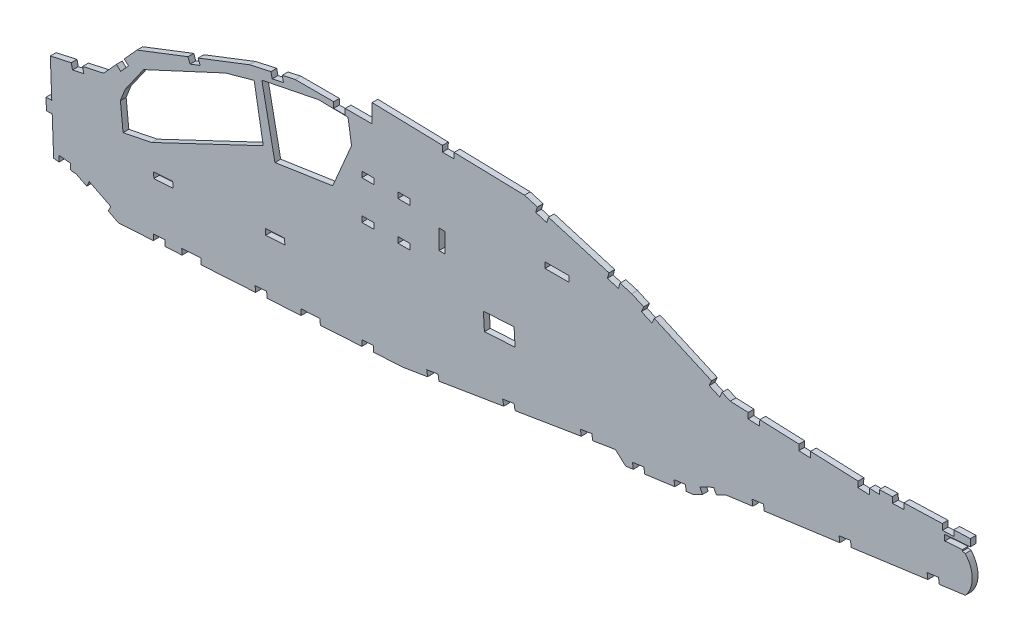
SolidWorks part; units mm, degrees
ref_plane "Front Plane" through (0, 0, 0) normal (0, 0, 1) x (1, 0, 0)
ref_plane "Top Plane" through (0, 0, 0) normal (0, 1, 0) x (1, 0, 0)
ref_plane "Right Plane" through (0, 0, 0) normal (1, 0, 0) x (0, 0, -1)
sketch "Sketch1" plane through (0, 0, 0) normal (0, 0, 1) x (1, 0, 0)
  line L0 (244.1166, 82.9113) -> (237.2526, 81.9698)
  line L1 (180.8712, 74.2361) -> (178.3627, 73.0223)
  line L2 (172.196, 70.0384) -> (170.43, 69.7961)
  line L3 (154.442, 67.6031) -> (151.7407, 70.0521)
  line L4 (151.7407, 70.0521) -> (145.7225, 69.0609)
  line L5 (95.7295, 60.8263) -> (87.8336, 60.347)
  line L6 (20.5725, 56.264) -> (17.8243, 57.6384)
  line L7 (9.3965, 61.8529) -> (7.8935, 62.0112)
  line L8 (3.4179, 62.4823) -> (3.0359, 72.4505)
  line L9 (2.538, 85.44) -> (8.0751, 86.66)
  line L10 (16.629, 88.5448) -> (19.9887, 92.2505)
  line L11 (25.41, 98.2302) -> (38.876, 103.4389)
  line L12 (55.2046, 109.7549) -> (57.4147, 110.2419)
  line L13 (57.4147, 110.2419) -> (60.79, 110.9856)
  line L14 (67.142, 112.3852) -> (70.2508, 112.3852)
  line L15 (70.2508, 112.3852) -> (77.3487, 112.3852)
  line L16 (87.4946, 112.3852) -> (87.4946, 117.2597)
  line L17 (87.4946, 117.2597) -> (106.0908, 116.7724)
  line L18 (182.0467, 96.2623) -> (186.8137, 96.0667)
  line L19 (241.1319, 94.854) -> (238.0856, 94.7537)
  line L20 (227.959, 94.4203) -> (224.9127, 94.32)
  line L21 (21.1257, 91.2197) -> (23.1872, 93.4936)
  line L22 (38.876, 103.4389) -> (41.5503, 104.4734) construction
  line L23 (61.118, 109.4973) -> (64.0946, 110.1532)
  line L24 (77.3487, 110.8612) -> (80.3967, 110.8612)
  line L25 (245.4465, 96.5209) -> (245.4465, 94.6474)
  line L26 (245.4465, 94.6474) -> (238.5747, 94.1291)
  line L27 (238.5747, 94.1291) -> (238.6893, 92.6094)
  line L28 (117.1507, 79.7033) -> (116.875, 84.2449)
  line L29 (243.349, 92.9609) -> (243.349, 92.6102)
  line L30 (243.349, 92.6102) -> (244.1166, 92.4387)
  line L31 (21.7429, 77.5049) -> (21.033, 84.485)
  line L32 (21.033, 84.485) -> (22.2949, 87.675)
  line L33 (22.2949, 87.675) -> (27.185, 94.6474)
  line L34 (27.185, 94.6474) -> (41.9439, 101.4899)
  line L35 (41.9439, 101.4899) -> (48.7926, 104.665)
  line L36 (48.7926, 104.665) -> (56.3594, 106.7696)
  line L37 (56.3594, 106.7696) -> (58.7557, 93.0264)
  line L38 (58.7557, 93.0264) -> (29.253, 79.0224)
  line L39 (29.253, 79.0224) -> (21.7429, 77.5049)
  line L40 (58.388, 107.8306) -> (61.8435, 90.7293)
  line L41 (61.8435, 90.7293) -> (77.0941, 93.0264)
  line L42 (77.0941, 93.0264) -> (82.0607, 104.665)
  line L43 (82.0607, 104.665) -> (81.1493, 110.7156)
  line L44 (81.1493, 110.7156) -> (73.3851, 110.861)
  line L45 (73.3851, 110.861) -> (58.388, 107.8306)
  line L46 (11.0517, 87.3159) -> (16.629, 88.5448)
  line L47 (8.0751, 86.66) -> (8.403, 85.1717)
  line L48 (62.6063, 109.8252) -> (62.2783, 111.3135) construction
  line L49 (80.3967, 112.3852) -> (87.4946, 112.3852)
  line L50 (80.3967, 110.8612) -> (80.3967, 112.3852)
  line L51 (77.3487, 110.8612) -> (77.3487, 112.3852)
  line L52 (64.0946, 110.1532) -> (63.7666, 111.6415)
  line L53 (42.1001, 103.052) -> (41.5503, 104.4734)
  line L54 (19.9887, 92.2505) -> (21.1257, 91.2197)
  line L55 (61.118, 109.4973) -> (60.79, 110.9856)
  line L56 (39.4258, 102.0175) -> (38.876, 103.4389)
  line L57 (22.0503, 94.5244) -> (23.1872, 93.4936)
  line L58 (63.7666, 111.6415) -> (67.142, 112.3852)
  line L59 (11.0517, 87.3159) -> (11.3796, 85.8276)
  line L60 (22.0503, 94.5244) -> (25.41, 98.2302)
  line L61 (41.5503, 104.4734) -> (55.2046, 109.7549)
  line L62 (8.403, 85.1717) -> (11.3796, 85.8276)
  line L63 (109.1388, 116.6926) -> (127.7349, 116.2053)
  line L64 (106.0908, 116.7724) -> (106.0498, 115.2091)
  line L65 (109.1388, 116.6926) -> (109.0999, 115.2091)
  line L66 (106.0498, 115.2091) -> (109.0999, 115.2091)
  line L67 (182.0467, 96.2623) -> (179.9032, 97.2146)
  line L68 (127.7349, 116.2053) -> (131.1284, 115.2001)
  line L69 (130.6956, 113.7389) -> (133.618, 112.8732)
  line L70 (39.4258, 102.0175) -> (42.1001, 103.052)
  line L71 (179.2844, 95.8218) -> (176.4989, 97.0593)
  line L72 (3.0359, 72.4505) -> (1.513, 72.3921)
  line L73 (186.7512, 94.544) -> (189.7967, 94.419)
  line L74 (159.2067, 106.4092) -> (156.0072, 107.8306)
  line L75 (2.9191, 75.4985) -> (2.538, 85.44)
  line L76 (1.513, 72.3921) -> (1.3962, 75.4401)
  line L77 (2.9191, 75.4985) -> (1.3962, 75.4401)
  line L78 (203.251, 95.3924) -> (215.8026, 94.8775)
  line L79 (189.8591, 95.9418) -> (200.2056, 95.5173)
  line L80 (186.8137, 96.0667) -> (186.7512, 94.544)
  line L81 (152.5276, 107.2719) -> (152.9604, 108.7331)
  line L82 (133.618, 112.8732) -> (134.0509, 114.3345)
  line L83 (149.6051, 108.1376) -> (150.0379, 109.5988)
  line L84 (130.6956, 113.7389) -> (131.1284, 115.2001)
  line L85 (134.0509, 114.3345) -> (150.0379, 109.5988)
  line L86 (145.5165, 70.5715) -> (142.5079, 70.0759)
  line L87 (149.6051, 108.1376) -> (152.5276, 107.2719)
  line L88 (104.9142, 63.8837) -> (101.9067, 63.3883)
  line L89 (152.9604, 108.7331) -> (156.0072, 107.8306)
  line L90 (161.3734, 103.779) -> (161.9922, 105.1717)
  line L91 (158.5879, 105.0165) -> (159.2067, 106.4092)
  line L92 (177.1177, 98.4521) -> (161.9922, 105.1717)
  line L93 (179.2844, 95.8218) -> (179.9032, 97.2146)
  line L94 (176.4989, 97.0593) -> (177.1177, 98.4521)
  line L95 (161.3734, 103.779) -> (158.5879, 105.0165)
  line L96 (124.9911, 67.1906) -> (121.9837, 66.6953)
  line L97 (6.3713, 63.727) -> (6.3713, 63.8874) construction
  line L98 (123.9343, 65.472) -> (126.1036, 51.0596) construction
  line L99 (4.8473, 62.3318) -> (4.8473, 63.8874)
  line L100 (7.8935, 63.5668) -> (7.8935, 62.0112)
  line L101 (18.5059, 59.0015) -> (12.8265, 61.8416)
  line L102 (4.8473, 63.8874) -> (7.8935, 63.5668)
  line L103 (12.1448, 60.4786) -> (9.3965, 61.8529)
  line L104 (4.8473, 62.3318) -> (3.4179, 62.4823)
  line L105 (101.9067, 63.3883) -> (102.1544, 61.8846)
  line L106 (17.8243, 57.6384) -> (18.5059, 59.0015)
  line L107 (121.9837, 66.6953) -> (122.2313, 65.1915)
  line L108 (104.9142, 63.8837) -> (105.1619, 62.3799)
  line L109 (124.9911, 67.1906) -> (125.2388, 65.6869)
  line L110 (142.5079, 70.0759) -> (142.7139, 68.5653)
  line L111 (145.5165, 70.5715) -> (145.7225, 69.0609)
  line L112 (142.7139, 68.5653) -> (125.2388, 65.6869)
  line L113 (122.2313, 65.1915) -> (105.1619, 62.3799)
  line L114 (102.1544, 61.8846) -> (95.7295, 60.8263)
  line L115 (189.8591, 95.9418) -> (189.7967, 94.419)
  line L116 (218.8481, 94.7525) -> (221.4099, 94.6474)
  line L117 (215.8026, 94.8775) -> (215.7402, 93.3547)
  line L118 (218.8481, 94.7525) -> (218.7856, 93.2298)
  line L119 (12.1448, 60.4786) -> (12.8265, 61.8416)
  line L120 (87.8336, 61.8738) -> (84.7856, 61.6888)
  line L121 (203.1885, 93.8697) -> (203.251, 95.3924)
  line L122 (200.1431, 93.9946) -> (200.2056, 95.5173)
  line L123 (32.7916, 58.5326) -> (29.7436, 58.3476)
  line L124 (29.7436, 58.3476) -> (29.7436, 56.8208)
  line L125 (32.7916, 58.5326) -> (32.7916, 57.0058)
  line L126 (200.1431, 93.9946) -> (203.1885, 93.8697)
  line L127 (84.7856, 61.6888) -> (84.7856, 60.162)
  line L128 (87.8336, 61.8738) -> (87.8336, 60.347)
  line L129 (29.7436, 56.8208) -> (20.5725, 56.264)
  line L130 (59.7504, 58.6423) -> (59.6581, 60.1635)
  line L131 (56.708, 58.4576) -> (56.6157, 59.9788)
  line L132 (56.708, 58.4576) -> (32.7916, 57.0058)
  line L133 (215.7402, 93.3547) -> (218.7856, 93.2298)
  line L134 (59.6581, 60.1635) -> (56.6157, 59.9788)
  line L135 (84.7856, 60.162) -> (59.7504, 58.6423)
  line L136 (156.2509, 69.3895) -> (159.2706, 69.8037)
  line L137 (167.2031, 70.8918) -> (170.2229, 71.306)
  line L138 (170.43, 69.7961) -> (170.2229, 71.306)
  line L139 (167.4102, 69.3819) -> (167.2031, 70.8918)
  line L140 (159.4777, 68.2938) -> (159.2706, 69.8037)
  line L141 (156.458, 67.8796) -> (156.2509, 69.3895)
  line L142 (156.458, 67.8796) -> (154.442, 67.6031)
  line L143 (167.4102, 69.3819) -> (159.4777, 68.2938)
  line L144 (174.0407, 72.624) -> (177.6989, 74.3941)
  line L145 (178.3627, 73.0223) -> (177.6989, 74.3941)
  line L146 (174.7045, 71.2522) -> (174.0407, 72.624)
  line L147 (174.7045, 71.2522) -> (172.196, 70.0384)
  line L148 (237.0455, 83.4797) -> (234.0258, 83.0655)
  line L149 (188.0197, 75.2166) -> (180.8712, 74.2361)
  line L150 (210.9841, 78.3666) -> (191.0394, 75.6308)
  line L151 (234.2329, 81.5556) -> (214.0038, 78.7808)
  line L152 (237.2526, 81.9698) -> (237.0455, 83.4797)
  line L153 (214.0038, 78.7808) -> (213.7967, 80.2907)
  line L154 (191.0394, 75.6308) -> (190.8323, 77.1407)
  line L155 (234.2329, 81.5556) -> (234.0258, 83.0655)
  line L156 (210.9841, 78.3666) -> (210.777, 79.8765)
  line L157 (188.0197, 75.2166) -> (187.8126, 76.7265)
  line L158 (190.8323, 77.1407) -> (187.8126, 76.7265)
  line L159 (213.7967, 80.2907) -> (210.777, 79.8765)
  line L160 (221.4099, 94.6474) -> (221.4099, 95.7295)
  line L161 (221.4099, 95.7295) -> (224.8625, 95.8432)
  line L162 (243.349, 92.9609) -> (238.6893, 92.6094)
  line L163 (224.8625, 95.8432) -> (224.9127, 94.32)
  line L164 (238.0354, 96.2769) -> (238.0856, 94.7537)
  line L165 (227.9089, 95.9435) -> (227.959, 94.4203)
  line L166 (241.0818, 96.3772) -> (241.1319, 94.854)
  line L167 (227.9089, 95.9435) -> (238.0354, 96.2769)
  line L168 (241.0818, 96.3772) -> (245.4465, 96.5209)
  line L169 (116.875, 84.2449) -> (124.9761, 84.7367)
  line L170 (124.9761, 84.7367) -> (125.2518, 80.1951)
  line L171 (125.2518, 80.1951) -> (117.1507, 79.7033)
  line L172 (87.9606, 99.4896) -> (94.3106, 99.4896) construction
  line L173 (139.4997, 102.1561) -> (133.1497, 102.1561)
  line L174 (139.4997, 102.1561) -> (139.4997, 103.6801)
  line L175 (139.4997, 103.6801) -> (133.1497, 103.6801)
  line L176 (133.1497, 102.1561) -> (133.1497, 103.6801)
  line L177 (106.6859, 97.4098) -> (105.1619, 97.4098)
  line L178 (106.6859, 97.4098) -> (106.6859, 92.2536)
  line L179 (106.6859, 92.2536) -> (105.1619, 92.2536)
  line L180 (105.1619, 97.4098) -> (105.1619, 92.2536)
  line L181 (84.7856, 98.7276) -> (87.9606, 98.7276)
  line L182 (84.7856, 98.7276) -> (84.7856, 100.2516)
  line L183 (84.7856, 100.2516) -> (87.9606, 100.2516)
  line L184 (87.9606, 98.7276) -> (87.9606, 100.2516)
  line L185 (91.1356, 99.4896) -> (91.1356, 106.7696) construction
  line L186 (94.3106, 98.7276) -> (94.3106, 100.2516)
  line L187 (97.4856, 100.2516) -> (94.3106, 100.2516)
  line L188 (97.4856, 98.7276) -> (97.4856, 100.2516)
  line L189 (97.4856, 98.7276) -> (94.3106, 98.7276)
  line L190 (87.9606, 88.5175) -> (87.9606, 90.0415)
  line L191 (94.3106, 88.5175) -> (94.3106, 90.0415)
  line L192 (91.1356, 89.2795) -> (91.1356, 96.5595) construction
  line L193 (97.4856, 90.0415) -> (94.3106, 90.0415)
  line L194 (84.7856, 88.5175) -> (84.7856, 90.0415)
  line L195 (87.9606, 89.2795) -> (94.3106, 89.2795) construction
  line L196 (84.7856, 90.0415) -> (87.9606, 90.0415)
  line L197 (84.7856, 88.5175) -> (87.9606, 88.5175)
  line L198 (97.4856, 88.5175) -> (97.4856, 90.0415)
  line L199 (97.4856, 88.5175) -> (94.3106, 88.5175)
  arc A2 (244.1166, 92.4387) -> (244.1166, 82.9113) centre (238.8301, 87.675) cw
  point P20 (181.428, 94.8695)
  point P21 (155.3885, 106.4379)
  point P22 (6.3713, 62.1986)
  point P29 (127.3021, 114.7441)
  point P34 (155.5744, 106.3694)
  point P69 (19.8701, 92.3867)
  point P70 (20.8779, 91.2293)
  point P101 (21.2542, 57.6271)
  point P102 (10.0782, 63.216)
  point P107 (4.8473, 62.1986)
  point P129 (95.7935, 62.357)
  point P130 (20.4802, 57.7852)
  dimension "D1" = 1.524
  dimension "D3" = 3.175
  dimension "D4" = 1.524
  dimension "D5" = 3.175
  dimension "D2" = 5.1562
  dimension "D6" = 1.524
extrude "Boss-Extrude1" add sketch "Sketch1" along normal blind 1.524
sketch "Sketch2" plane through (-3.3273, 54.8132, 0) normal (0.0606, -0.9982, 0) x (-0.9982, -0.0606, 0)
  line L6 (-40.7177, -1.524) -> (-40.7177, 0)
  line L7 (-72.2201, -1.524) -> (-72.2201, 0)
  line L8 (-45.7977, -1.524) -> (-45.7977, 0)
  line L9 (-77.3001, -1.524) -> (-77.3001, 0)
  line L10 (-40.7177, -1.524) -> (-45.7977, -1.524)
  line L11 (-40.7177, 0) -> (-45.7977, 0)
  line L12 (-72.2201, -1.524) -> (-77.3001, -1.524)
  line L13 (-72.2201, 0) -> (-77.3001, 0)
extrude "Cut-Extrude1" cut sketch "Sketch2" against normal blind 1.524
sketch "Sketch3" plane through (0, 0, 1.524) normal (0, 0, 1) x (1, 0, 0)
  line L0 (29.7786, 72.5999) -> (29.8709, 71.0787)
  line L1 (29.8709, 71.0787) -> (34.9416, 71.3865)
  line L2 (34.9416, 71.3865) -> (34.8492, 72.9077)
  line L3 (34.8492, 72.9077) -> (29.7786, 72.5999)
  line L4 (64.3752, 74.7) -> (64.4675, 73.1788)
  line L5 (64.4675, 73.1788) -> (59.3969, 72.871)
  line L6 (59.3969, 72.871) -> (59.3045, 74.3922)
  line L7 (59.3045, 74.3922) -> (64.3752, 74.7)
extrude "Cut-Extrude2" cut sketch "Sketch3" against normal blind 1.524
